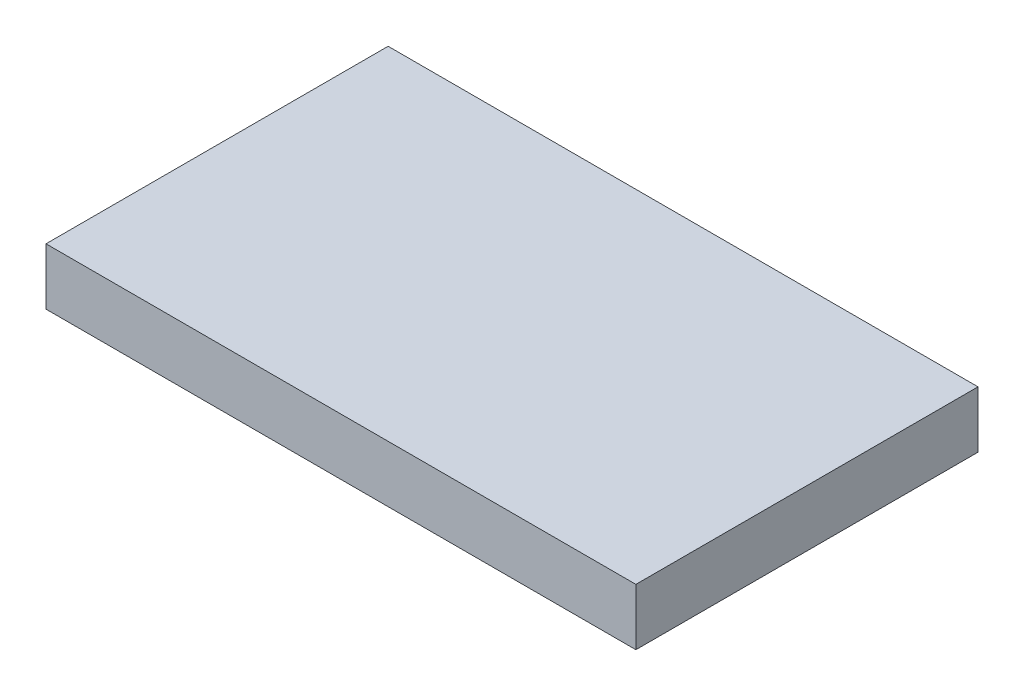
SolidWorks part; units mm, degrees
ref_plane "Спереди" through (0, 0, 0) normal (0, 0, 1) x (1, 0, 0)
ref_plane "Сверху" through (0, 0, 0) normal (0, 1, 0) x (1, 0, 0)
ref_plane "Справа" through (0, 0, 0) normal (1, 0, 0) x (0, 0, -1)
sketch "Эскиз1" plane through (0, 0, 0) normal (0, 1, 0) x (1, 0, 0)
  line L1 (25, -14.5) -> (-25, -14.5)
  line L2 (25, -14.5) -> (25, 14.5)
  line L3 (25, 14.5) -> (-25, 14.5)
  line L4 (-25, -14.5) -> (-25, 14.5)
  line L5 (25, -14.5) -> (-25, 14.5) construction
  line L6 (25, 14.5) -> (-25, -14.5) construction
  point P0 (0, 0)
extrude "Бобышка-Вытянуть1" add sketch "Эскиз1" along normal blind 4.8
